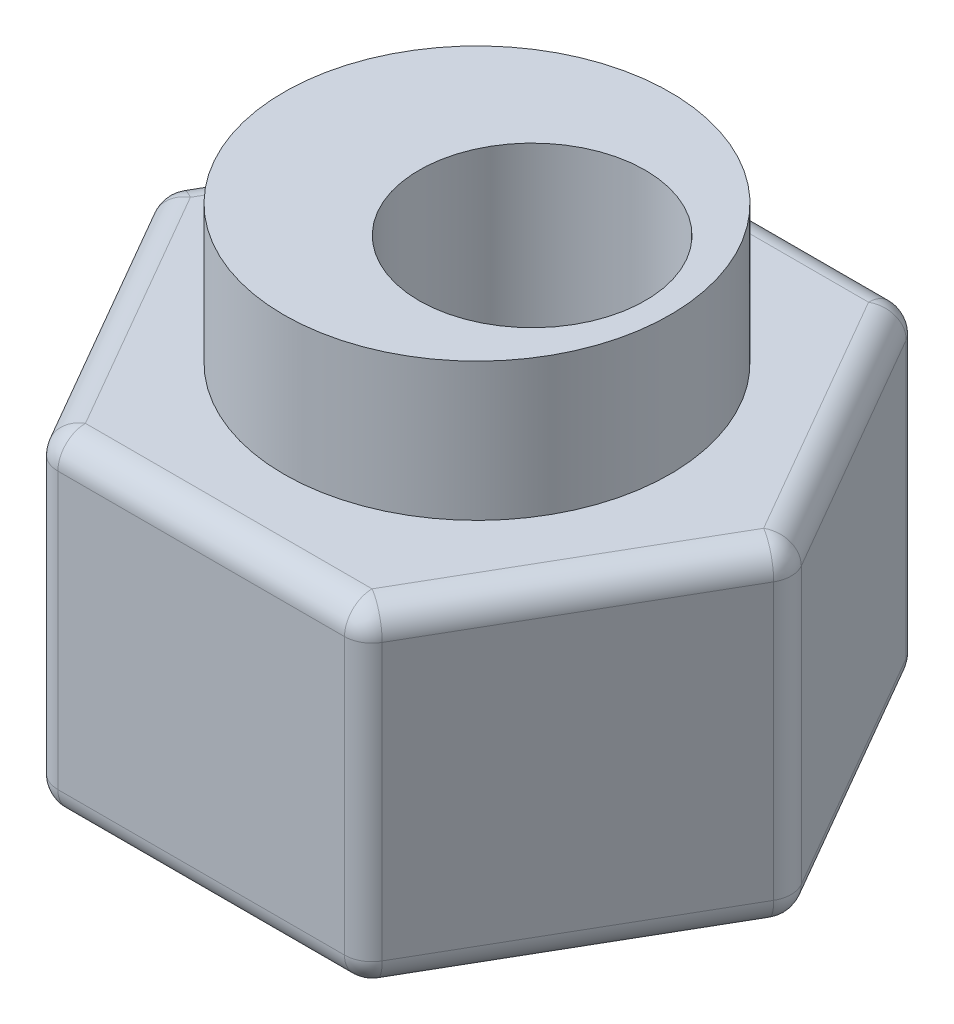
SolidWorks part; units mm, degrees
ref_plane "Front Plane" through (0, 0, 0) normal (0, 0, 1) x (1, 0, 0)
ref_plane "Top Plane" through (0, 0, 0) normal (0, 1, 0) x (1, 0, 0)
ref_plane "Right Plane" through (0, 0, 0) normal (1, 0, 0) x (0, 0, -1)
sketch "Sketch1" plane through (0, 0, 0) normal (0, 1, 0) x (1, 0, 0)
  line L0 (-55, 0) -> (55, 0) construction
  line L1 (-2.8868, 5) -> (-5.7735, 0)
  line L2 (-5.7735, 0) -> (-2.8868, -5)
  line L3 (-2.8868, -5) -> (2.8868, -5)
  line L4 (2.8868, -5) -> (5.7735, 0)
  line L5 (5.7735, 0) -> (2.8868, 5)
  line L6 (2.8868, 5) -> (-2.8868, 5)
  circle A0 centre (0, 0) radius 5 construction
  dimension "D1" = 10
extrude "Boss-Extrude1" add sketch "Sketch1" along normal blind 6
sketch "Sketch2" plane through (0, 6, 0) normal (0, 1, 0) x (1, 0, 0)
  circle A0 centre (0, 0) radius 3.5
  dimension "D1" = 7
extrude "Boss-Extrude2" add sketch "Sketch2" along normal blind 2.5
sketch "Sketch4" plane through (0, 8.5, 0) normal (0, 1, 0) x (1, 0, 0)
  line L0 (0, 0) -> (1, 0) construction
  circle A0 centre (1, 0) radius 2.05
  dimension "D1" = 4.1
  dimension "D2" = 1
extrude "Cut-Extrude1" cut sketch "Sketch4" against normal through all
fillet "Fillet1" radius 0.5 18 edges at (2.8868, 3, 5) (-2.8868, 3, 5) (-5.7735, 3, 0) (-2.8868, 3, -5) (2.8868, 3, -5) (5.7735, 3, 0) (4.3301, 6, 2.5) (0, 6, 5) (-4.3301, 6, 2.5) (-4.3301, 6, -2.5) (0, 6, -5) (4.3301, 6, -2.5) (0, 0, -5) (-4.3301, 0, -2.5) (-4.3301, 0, 2.5) (0, 0, 5) (4.3301, 0, 2.5) (4.3301, 0, -2.5)
